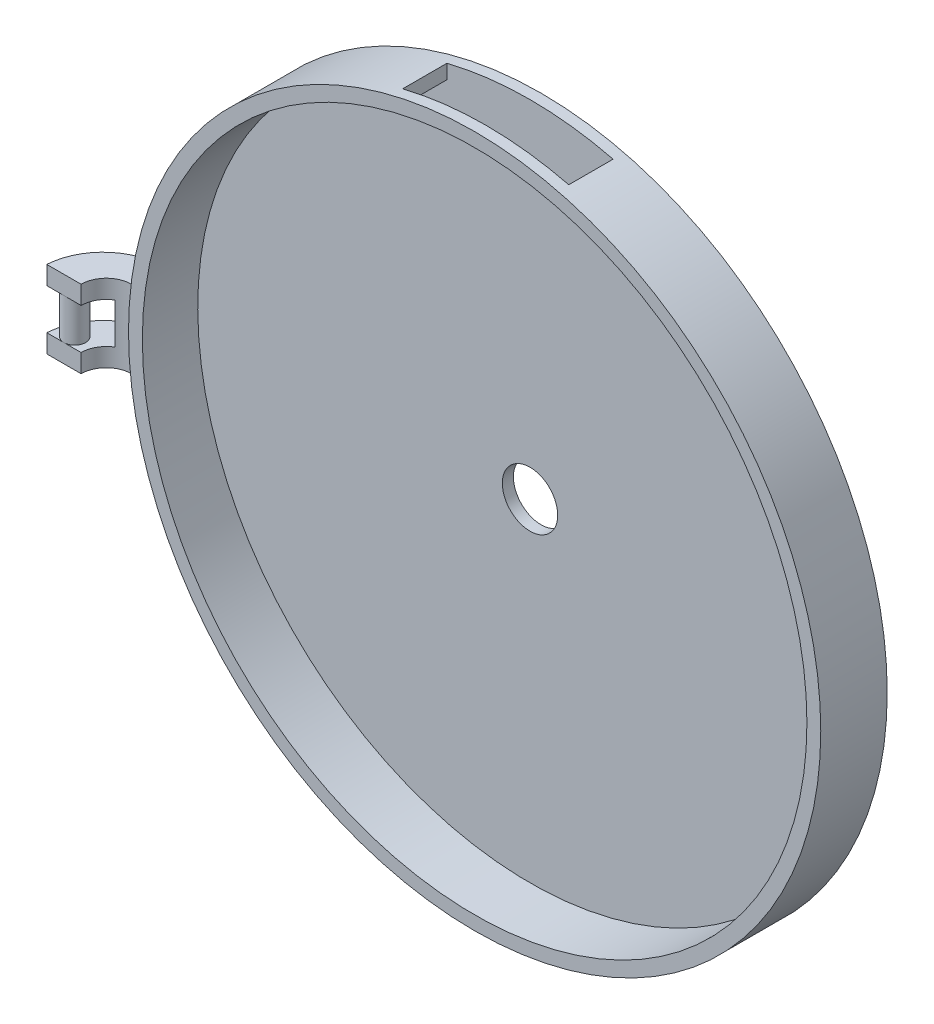
SolidWorks part; units mm, degrees
ref_plane "Front Plane" through (0, 0, 0) normal (0, 0, 1) x (1, 0, 0)
ref_plane "Top Plane" through (0, 0, 0) normal (0, 1, 0) x (1, 0, 0)
ref_plane "Right Plane" through (0, 0, 0) normal (1, 0, 0) x (0, 0, -1)
sketch "Sketch1" plane through (0, 0, 0) normal (0, 0, 1) x (1, 0, 0)
  circle A0 centre (0, 0) radius 79.375
  dimension "D1" = 158.75
extrude "Boss-Extrude1" add sketch "Sketch1" along normal blind 15.24
sketch "Sketch3" plane through (0, 0, 15.24) normal (0, 0, 1) x (1, 0, 0)
  circle A0 centre (0, 0) radius 76.2
  dimension "D1" = 152.4
extrude "Cut-Extrude1" cut sketch "Sketch3" against normal blind 12.7
sketch "Sketch4" plane through (0, 0, 0) normal (0, 1, 0) x (1, 0, 0)
  line L1 (-19.05, -2.54) -> (19.05, -2.54)
  line L2 (-19.05, -2.54) -> (-19.05, -12.7)
  line L3 (-19.05, -12.7) -> (19.05, -12.7)
  line L4 (19.05, -2.54) -> (19.05, -12.7)
  dimension "D1" = 38.1
  dimension "D2" = 19.05
  dimension "D3" = 10.16
  dimension "D4" = 2.54
extrude "Cut-Extrude2" cut sketch "Sketch4" against normal blind 12.7 from surface starting at face at (79.375, 0, 15.24)
sketch "Sketch10" plane through (0, 0, 0) normal (0, 1, 0) x (1, 0, 0)
  line L2 (-79.375, 0) -> (-79.375, -15.24) construction
  line L3 (-79.375, -7.2915) -> (-76.5248, -7.2915)
  line L4 (-76.5248, -7.2915) -> (-76.5248, -15.24)
  line L5 (-93.1494, -20.2066) -> (-85.2754, -20.2066)
  arc A0 (-79.375, -7.2915) -> (-93.1494, -20.2066) centre (-79.375, -21.0945) ccw
  arc A1 (-85.2754, -20.2066) -> (-76.5248, -15.24) centre (-79.4907, -20.2066) cw
  dimension "D3" = 13.803
  dimension "D4" = 5.7848
  dimension "D1" = 7.9485
  dimension "D2" = 7.874
  dimension "D5" = 76.5248
  dimension "D6" = 7.2915
extrude "Boss-Extrude4" add sketch "Sketch10" along normal mid plane 17.78
sketch "Sketch12" plane through (0, 0, 0) normal (1, 0, 0) x (0, 0, -1)
  line L0 (-20.2066, 0) -> (-15.24, 0) construction
  line L1 (-20.2066, 8.89) -> (-20.2066, -8.89) construction
  line L2 (-15.24, 79.375) -> (-15.24, -79.375) construction
  line L4 (-20.2066, -4.6698) -> (-15.24, -4.6698)
  line L5 (-20.2066, -4.6698) -> (-20.2066, 4.6698)
  line L6 (-20.2066, 4.6698) -> (-15.24, 4.6698)
  line L7 (-15.24, -4.6698) -> (-15.24, 4.6698)
  line L8 (-20.2066, -4.6698) -> (-15.24, 4.6698) construction
  line L9 (-20.2066, 4.6698) -> (-15.24, -4.6698) construction
  point P6 (-17.7233, 0)
  dimension "D1" = 4.6698
extrude "Cut-Extrude4" cut sketch "Sketch12" against normal blind 127
sketch "Sketch14" plane through (0, 0, 15.24) normal (0, 0, 1) x (1, 0, 0)
  line L0 (-91.8749, 4.6698) -> (-91.8749, -4.6698)
  line L1 (-91.8749, -4.6698) -> (-82.4565, -4.6698)
  line L2 (-82.4565, -4.6698) -> (-82.4565, 4.6698)
  line L3 (-82.4565, 4.6698) -> (-91.8749, 4.6698)
extrude "Cut-Extrude5" cut sketch "Sketch14" against normal blind 12.7
sketch "Sketch17" plane through (0, 4.6698, 0) normal (0, -1, 0) x (1, 0, 0)
  line L0 (-77.0857, 15.24) -> (-96.8071, 15.24) construction
  line L1 (79.375, 15.24) -> (-79.375, 15.24) construction
  line L2 (-89.2124, 20.2066) -> (-89.2124, 15.24) construction
  line L3 (-93.1494, 20.2066) -> (-85.2754, 20.2066) construction
  circle A0 centre (-89.2124, 17.7233) radius 2.4833
extrude "Boss-Extrude5" add sketch "Sketch17" along normal blind 12.7
sketch "Sketch18" plane through (0, 0, 0) normal (0, 0, -1) x (-1, 0, 0)
  circle A0 centre (0, 0) radius 6.35
  circle A1 centre (0, 0) radius 79.375 construction
  dimension "D1" = 12.7
extrude "Cut-Extrude6" cut sketch "Sketch18" against normal up to next
